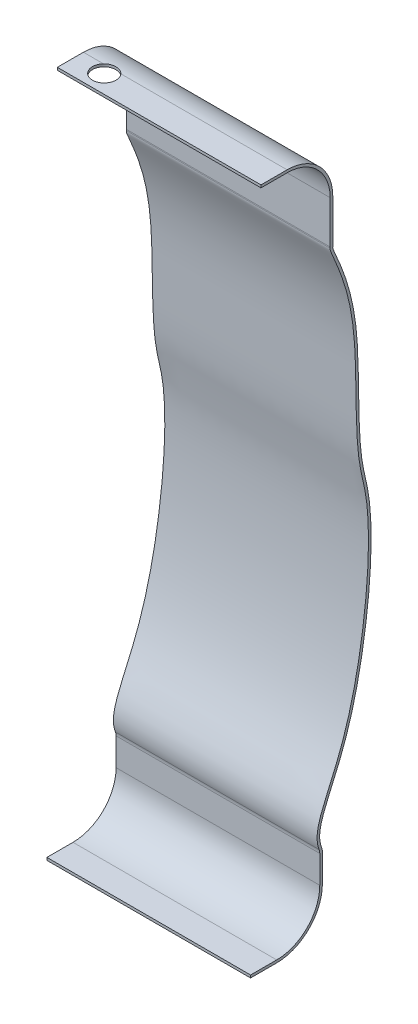
SolidWorks part; units mm, degrees
ref_plane "Front Plane" through (0, 0, 0) normal (0, 0, 1) x (1, 0, 0)
ref_plane "Top Plane" through (0, 0, 0) normal (0, 1, 0) x (1, 0, 0)
ref_plane "Right Plane" through (0, 0, 0) normal (1, 0, 0) x (0, 0, -1)
sketch "Sketch2" plane through (0, 0, 0) normal (1, 0, 0) x (0, 0, -1)
  line L0 (0, 0) -> (50000, 0) construction
  line L1 (-8.7551, 52.21) -> (49991.2449, 52.21) construction
  line L2 (0.7977, 52.21) -> (2.7977, 52.21)
  line L3 (6.2977, 48.71) -> (6.2977, 45.4405)
  line L4 (2, 0) -> (0, 0)
  line L5 (5.5, 3.5) -> (5.5, 5.6095)
  line L6 (0.7977, 52.01) -> (2.7977, 52.01)
  line L7 (6.0977, 48.71) -> (6.0977, 45.4405)
  line L8 (5.3, 3.5) -> (5.3, 5.6095)
  line L9 (2, 0.2) -> (0, 0.2)
  line L10 (0.7977, 52.21) -> (0.7977, 52.01)
  line L11 (0, 0.2) -> (0, 0)
  arc A0 (5.5, 3.5) -> (2, 0) centre (2, 3.5) cw
  arc A1 (2.7977, 52.21) -> (6.2977, 48.71) centre (2.7977, 48.71) cw
  arc A2 (5.5, 5.6095) -> (5.4347, 5.965) centre (4.5, 5.6095) ccw
  arc A3 (6.2977, 45.4405) -> (6.2927, 45.3413) centre (5.2977, 45.4405) cw
  arc A4 (2.7977, 52.01) -> (6.0977, 48.71) centre (2.7977, 48.71) cw
  arc A5 (6.0977, 45.4405) -> (6.0937, 45.3611) centre (5.2977, 45.4405) cw
  arc A6 (5.3, 5.6095) -> (5.2477, 5.8939) centre (4.5, 5.6095) ccw
  arc A7 (5.3, 3.5) -> (2, 0.2) centre (2, 3.5) cw
  arc A8 (6.2977, 45.4405) -> (6.2927, 45.3413) centre (5.2977, 45.4405) cw construction
  spline S0 degree 3 poles (6.2927, 45.3413) (6.2596, 45.0092) (8.7455, 41.1908) (8.0545, 31.3477) (9.796, 25.3216) (8.0687, 10.857) (4.7903, 7.6592) (5.4347, 5.965) knots 0.006984 0.006984 0.006984 0.006984 0.231916 0.408888 0.457655 0.719584 0.994356 0.994356 0.994356 0.994356
  spline S1 degree 1 poles (6.0937, 45.3611) (5.2477, 5.8939) knots 0 0 1 1 construction
  spline S2 degree 3 poles (6.0937, 45.3611) (6.0826, 45.2494) (6.1529, 45.0578) (6.3391, 44.6174) (6.6162, 43.9867) (7.0456, 42.8957) (7.6215, 41.0743) (8.03, 38.1457) (8.0622, 35.2285) (8.1033, 32.9353) (8.1783, 31.3036) (8.3406, 29.8223) (8.6381, 28.5924) (8.8913, 27.3372) (9.0188, 25.8339) (9.045, 24.1786) (8.9522, 21.8223) (8.6234, 18.7363) (7.9712, 15.1955) (7.1363, 12.2856) (6.2432, 10.1304) (5.2325, 7.9362) (4.9332, 6.7209) (5.2477, 5.8939) knots 0.006984 0.006984 0.006984 0.006984 0.03784 0.068695 0.09955 0.130406 0.192117 0.253827 0.315538 0.346393 0.377249 0.408104 0.43896 0.469815 0.50067 0.531526 0.562381 0.624092 0.685802 0.747513 0.809224 0.870935 0.994356 0.994356 0.994356 0.994356
  point P13 (5.5, 0)
  point P16 (6.2977, 52.21)
  dimension "D4" = 3.5
  dimension "D5" = 1
  dimension "D3" = 3.5
  dimension "D2" = 1
  dimension "D1" = 52.21
  dimension "D6" = 2
  dimension "D7" = 2
  dimension "D8" = 0.2
extrude "Boss-Extrude1" add sketch "Sketch2" along normal blind 15.6
hole_wizard "M1.6 Clearance Hole1" positions "Sketch6" profile "Sketch5" hole size "M1.6" standard "ANSI Metric"
sketch "Sketch6" plane through (0, 52.21, 0) normal (0, 1, 0) x (1, 0, 0)
  point P13 (2.2009, 2.1906)
sketch "Sketch5" plane through (2.2009, 52.21, -2.1906) normal (1, 0, 0) x (0, 0, 1)
  line L0 (0, 0) -> (0, 2.1208)
  line L1 (0, 2.1208) -> (0.9, 1.58)
  line L2 (0.9, 1.58) -> (0.9, 0)
  line L5 (0.9, 0) -> (0, 0)
  line L10 (0, 2.1208) -> (-0.9, 1.58) construction
  line L11 (0, -6.35) -> (0, 107.95) construction
  dimension "Hole Dia." = 1.8
  dimension "Hole Depth" = 1.58
  dimension "Drill Angle" = 118
